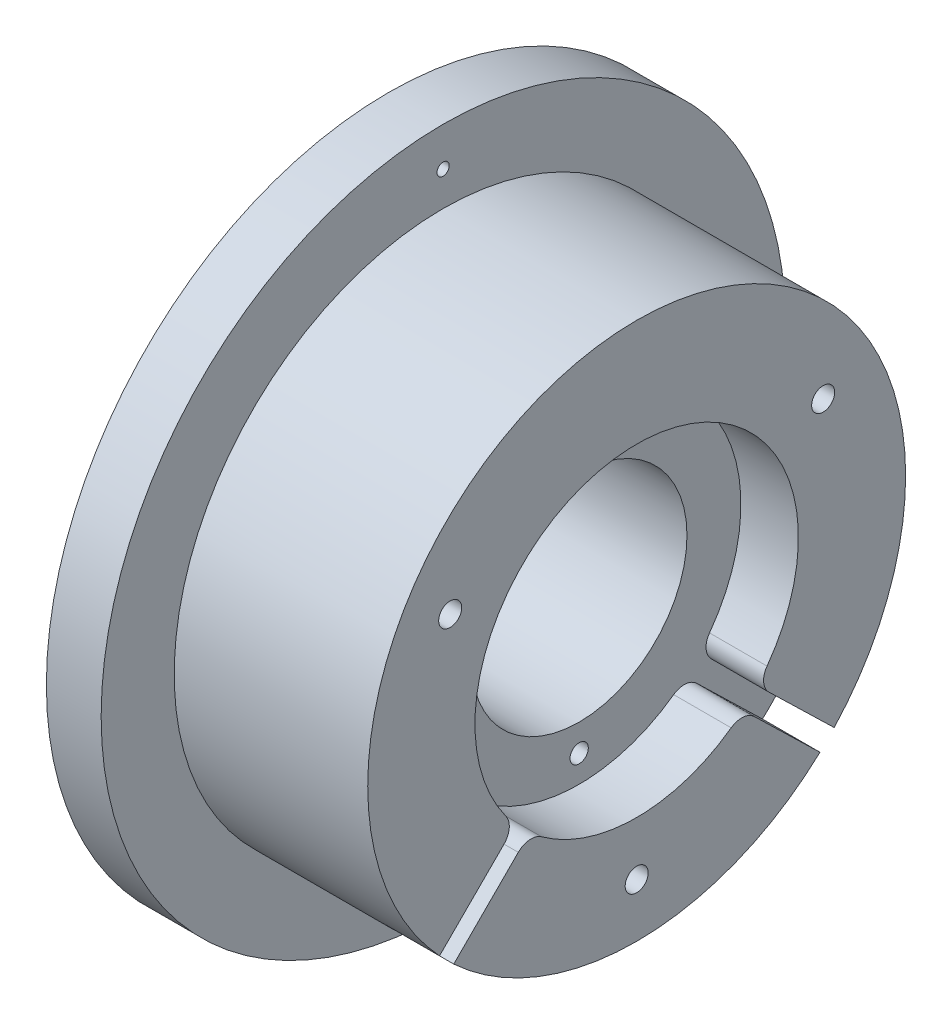
SolidWorks part; units mm, degrees
ref_plane "Front" through (0, 0, 0) normal (0, 0, 1) x (1, 0, 0)
ref_plane "Top" through (0, 0, 0) normal (0, 1, 0) x (1, 0, 0)
ref_plane "Right" through (0, 0, 0) normal (1, 0, 0) x (0, 0, -1)
sketch "Sketch1" plane through (0, 0, 0) normal (0, 0, 1) x (1, 0, 0)
  line L0 (0, 0) -> (0, 23.7871)
  line L1 (0, 23.7871) -> (3.81, 23.7871)
  line L2 (3.81, 23.7871) -> (3.81, 18.7071)
  line L3 (3.81, 18.7071) -> (17.272, 18.7071)
  line L4 (17.272, 18.7071) -> (17.272, 11.25)
  line L5 (17.272, 11.25) -> (13.272, 11.25)
  line L6 (13.272, 11.25) -> (13.272, 0)
  line L7 (13.272, 0) -> (0, 0)
  line L8 (13.272, 7.5) -> (0, 7.5)
  dimension "D1" = 23.7871
  dimension "D2" = 3.81
  dimension "D3" = 13.462
  dimension "D4" = 4
  dimension "D5" = 11.25
  dimension "D6" = 18.7071
  dimension "D7" = 7.5
revolve "Revolve1" add sketch "Sketch1" angle 360 about L7
sketch "Sketch2" plane through (17.272, 0, 0) normal (1, 0, 0) x (0, 0, -1)
  line L0 (0, 0) -> (-13.2279, -13.2279) construction
  line L1 (0, 0) -> (0, -18.7071) construction
  line L2 (0.3171, 0.3268) -> (13.7426, -12.7005)
  line L3 (-13.7229, -12.7329) -> (-12.7329, -13.7229)
  line L4 (-13.7229, -12.7329) -> (-0.495, 0.495)
  line L5 (-0.495, 0.495) -> (0.495, -0.495)
  line L6 (0.495, -0.495) -> (-12.7329, -13.7229)
  line L7 (12.7677, -13.7053) -> (13.7426, -12.7005)
  line L8 (12.7677, -13.7053) -> (-0.6578, -0.6779)
  line L9 (-0.6578, -0.6779) -> (0.3171, 0.3268)
  circle A0 centre (0, 0) radius 18.7071 construction
  circle A1 centre (-12.9709, 7.4887) radius 0.315
  circle A2 centre (12.9709, 7.4888) radius 0.315
  circle A3 centre (0, 0) radius 18.7071 construction
  circle A4 centre (0, -14.9775) radius 0.315
  circle A5 centre (0, 0) radius 11.25 construction
  point P6 (0, 0)
  point P14 (-13.2279, -13.2279)
  circle M8 centre (0, 0) radius 18.7071
  circle M9 centre (0, 0) radius 11.25
  dimension "D4" = 0.63
  dimension "D1" = 45
  dimension "D2" = 1.4
  dimension "D3" = 14.9775
  dimension "D5" = 3
  dimension "D6" = 2
extrude "Cut-Extrude1" cut sketch "Sketch2" against normal up to surface (4 mm away) contours L8 L9 L5 L4 L6 M9 | L6 L4 M9 M8 | L8 L2 M8 M9 | L9 L5 L6 L8 L2 M9 | A4 | A1 | A2 up to face at (13.272, 7.5, 0)
sketch "Sketch3" plane through (3.81, 0, 0) normal (1, 0, 0) x (0, 0, -1)
  line L0 (0, 0) -> (0, 21.082) construction
  circle A0 centre (0, 21.082) radius 0.425
  dimension "D1" = 0.85
  dimension "D2" = 21.082
extrude "Cut-Extrude2" cut sketch "Sketch3" against normal through all
sketch "Sketch4" plane through (13.272, 0, 0) normal (1, 0, 0) x (0, 0, -1)
  line L0 (0, -9.375) -> (0, 9.375) construction
  circle A0 centre (0, 9.375) radius 0.635
  circle A1 centre (0, -9.375) radius 0.635
  point P6 (0, 0)
  dimension "D2" = 1.27
  dimension "D1" = 18.75
extrude "Cut-Extrude3" cut sketch "Sketch4" against normal through all
fillet "Fillet1" radius 1.25 4 edges at (15.272, -7.4446, 8.4345) (15.272, -8.4345, 7.4446) (15.272, -8.4846, -7.3874) (15.272, -7.5011, -8.3843)
hole_wizard "M2x0.4 Tapped Hole1" positions "3DSketch2" profile "Sketch5" tap size "M2x0.4" standard "ANSI Metric"
sketch3d "3DSketch2"
  line L0 (13.272, 7.4887, 12.9709) -> (17.272, 7.4887, 12.9709) construction
  line L1 (13.272, 7.4888, -12.9709) -> (17.272, 7.4888, -12.9709) construction
  line L2 (13.272, -14.9775, 0) -> (17.272, -14.9775, 0) construction
  point P0 (17.272, 7.4887, 12.9709)
  point P4 (17.272, 7.4888, -12.9709)
  point P8 (17.272, -14.9775, 0)
sketch "Sketch5" plane through (17.272, 7.4887, 12.9709) normal (0, 1, 0) x (0, 0, -1)
  line L0 (0, 0) -> (0, 6.8307)
  line L1 (0, 6.8307) -> (0.8, 6.35)
  line L2 (0.8, 6.35) -> (0.8, 0)
  line L5 (0.8, 0) -> (0, 0)
  line L10 (0, 6.8307) -> (-0.8, 6.35) construction
  line L11 (0, -6.35) -> (0, 107.95) construction
  dimension "Tap Drill Dia." = 1.6
  dimension "Tap Drill Depth" = 6.35
  dimension "Drill Angle" = 118
cosmetic thread "Hole Thread1" parameters "D1"=4, "D2"=2
cosmetic thread "Hole Thread2" parameters "D1"=4, "D2"=2
cosmetic thread "Hole Thread3" parameters "D1"=4, "D2"=2
